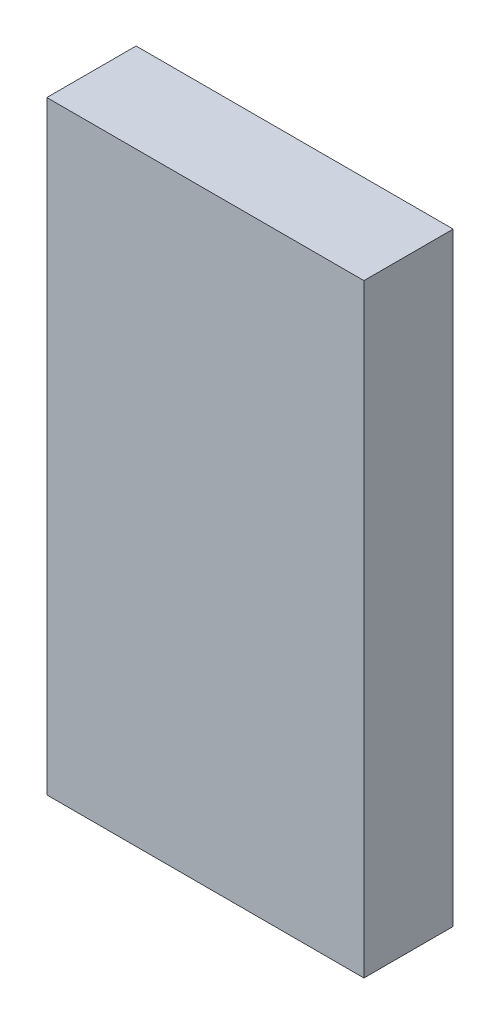
SolidWorks part; units mm, degrees
ref_plane "Płaszczyzna przednia" through (0, 0, 0) normal (0, 0, 1) x (1, 0, 0)
ref_plane "Płaszczyzna górna" through (0, 0, 0) normal (0, 1, 0) x (1, 0, 0)
ref_plane "Płaszczyzna prawa" through (0, 0, 0) normal (1, 0, 0) x (0, 0, -1)
sketch "Szkic1" plane through (0, 0, 0) normal (0, 0, 1) x (1, 0, 0)
  line L1 (0, 0) -> (53.3, 0)
  line L2 (0, 0) -> (0, 101.52)
  line L3 (0, 101.52) -> (53.3, 101.52)
  line L4 (53.3, 0) -> (53.3, 101.52)
  dimension "D1" = 53.3
  dimension "D2" = 101.52
extrude "Dodanie-wyciągnięcie1" add sketch "Szkic1" along normal blind 15
